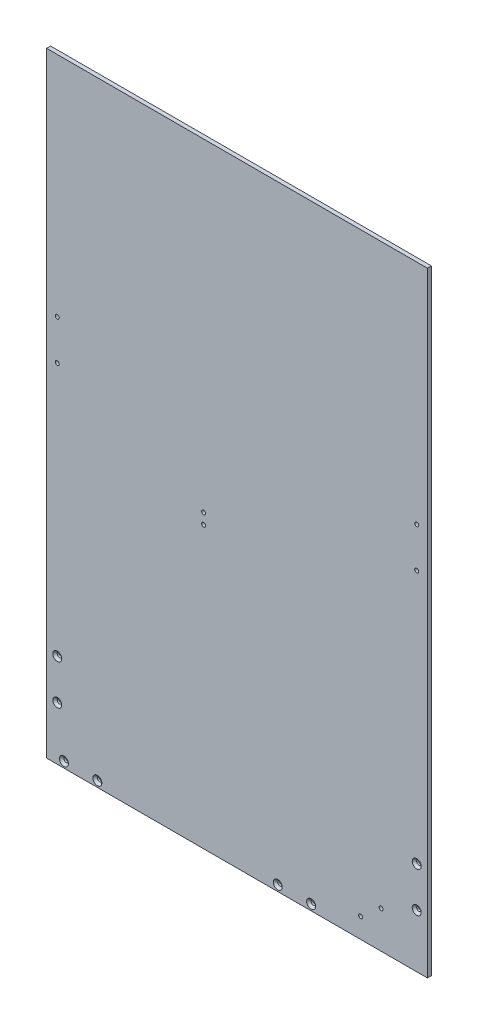
SolidWorks part; units mm, degrees
material "ABS PC"
ref_plane "前视基准面" through (0, 0, 0) normal (0, 0, 1) x (1, 0, 0)
ref_plane "上视基准面" through (0, 0, 0) normal (0, 1, 0) x (1, 0, 0)
ref_plane "右视基准面" through (0, 0, 0) normal (1, 0, 0) x (0, 0, -1)
sketch "草图1" plane through (0, 0, 0) normal (0, 0, 1) x (1, 0, 0)
  line L1 (-142.5, 230) -> (142.5, 230)
  line L2 (-142.5, 230) -> (-142.5, -230)
  line L3 (-142.5, -230) -> (142.5, -230)
  line L4 (142.5, 230) -> (142.5, -230)
  line L5 (-142.5, 230) -> (142.5, -230) construction
  line L6 (-142.5, -230) -> (142.5, 230) construction
  point P0 (0, 0)
  dimension "D1" = 460
  dimension "D2" = 285
extrude "凸台-拉伸1" add sketch "草图1" along normal blind 3
sketch "草图2" plane through (0, 0, 3) normal (0, 0, 1) x (1, 0, 0)
  line L0 (0, 230) -> (0, -230) construction
  line L1 (142.5, 230) -> (-142.5, 230) construction
  line L2 (-142.5, -230) -> (142.5, -230) construction
  line L3 (-134.5, 230) -> (-134.5, -230) construction
  line L4 (134.5, 230) -> (134.5, -230) construction
  line L5 (-142.5, 230) -> (-142.5, -230) construction
  circle A0 centre (-134.5, -190) radius 1.5
  circle A1 centre (134.5, -190) radius 1.5
  circle A2 centre (-134.5, -160) radius 1.5
  circle A3 centre (134.5, -160) radius 1.5
  circle A4 centre (-134.5, 30) radius 1.5
  circle A5 centre (134.5, 30) radius 1.5
  circle A6 centre (-134.5, 60) radius 1.5
  circle A7 centre (134.5, 60) radius 1.5
  dimension "D2" = 30
  dimension "D6" = 3
  dimension "D1" = 8
  dimension "D3" = 30
  dimension "D4" = 40
  dimension "D5" = 190
extrude "切除-拉伸1" cut sketch "草图2" against normal through all
sketch "草图4" plane through (0, 0, 3) normal (0, 0, 1) x (1, 0, 0)
  line L0 (-142.5, -230) -> (142.5, -230) construction
  line L1 (142.5, -230) -> (142.5, 230) construction
  line L2 (-129.5, -225.5) -> (-104.5, -225.5) construction
  line L3 (-142.5, -230) -> (142.5, -230) construction
  line L5 (55.5, -225.5) -> (30.5, -225.5) construction
  circle A0 centre (-129.5, -225.5) radius 1.5
  circle A2 centre (-104.5, -225.5) radius 1.5
  circle A3 centre (30.5, -225.5) radius 1.5
  circle A5 centre (55.5, -225.5) radius 1.5
  dimension "D2" = 25
  dimension "D6" = 160
  dimension "D4" = 3
  dimension "D3" = 25
  dimension "D5" = 4.5
  dimension "D7" = 87
  dimension "D11" = 4.5
extrude "切除-拉伸2" cut sketch "草图4" against normal through all
sketch "草图6" plane through (0, 0, 0) normal (0, 0, -1) x (-1, 0, 0)
  line L0 (25, 190) -> (25, -190) construction
  line L1 (142.5, 230) -> (142.5, -230) construction
  line L2 (142.5, -230) -> (-142.5, -230) construction
  circle A0 centre (25, -20) radius 1.5
  circle A1 centre (25, -12) radius 1.5
  dimension "D1" = 3
  dimension "D2" = 8
  dimension "D3" = 210
  dimension "D4" = 117.5
extrude "切除-拉伸3" cut sketch "草图6" against normal through all
sketch "草图7" plane through (0, 0, 0) normal (0, 0, -1) x (-1, 0, 0)
  line L0 (67.5, 230) -> (67.5, -230) construction
  line L1 (-142.5, 230) -> (142.5, 230) construction
  line L2 (142.5, -230) -> (-142.5, -230) construction
  line L3 (142.5, 230) -> (142.5, -230) construction
  circle A0 centre (67.5, -157) radius 9.5 construction
  circle A1 centre (67.5, -166.5) radius 1.5
  circle A2 centre (59.2728, -152.25) radius 1.5
  circle A3 centre (75.7272, -152.25) radius 1.5
  circle A4 centre (67.5, -157) radius 6.75
  point P18 (67.5, -157)
  dimension "D1" = 19
  dimension "D4" = 3
  dimension "D6" = 13.5
  dimension "D2" = 75
  dimension "D3" = 73
  dimension "D5" = 3
extrude "切除-拉伸4" [suppressed] cut sketch "草图7" against normal through all
sketch "草图8" plane through (0, 0, 0) normal (0, 0, -1) x (-1, 0, 0)
  line L0 (142.5, -230) -> (-142.5, -230) construction
  line L3 (-142.5, -230) -> (-142.5, 230) construction
  line L5 (-92.5, -215) -> (-107.8209, -202.1442) construction
  line L6 (-142.5, -230) -> (-142.5, 230) construction
  circle A2 centre (-107.8209, -202.1442) radius 1.5
  circle A3 centre (-92.5, -215) radius 1.5
  dimension "D9" = 3
  dimension "D7" = 50
  dimension "D8" = 50
  dimension "D10" = 15
  dimension "D11" = 20
extrude "切除-拉伸5" cut sketch "草图8" against normal through all
hole_wizard "M3 六角凹锥坑螺钉的锥形沉头孔1" positions "3D草图1" profile "草图9" countersink size "M3" standard "ISO" end condition through all
sketch3d "3D草图1"
  line L0 (-134.5, -160, 0) -> (-134.5, -160, 3) construction
  line L1 (-134.5, -190, 0) -> (-134.5, -190, 3) construction
  line L2 (134.5, -160, 0) -> (134.5, -160, 3) construction
  line L3 (134.5, -190, 0) -> (134.5, -190, 3) construction
  line L4 (-129.5, -225.5, 0) -> (-129.5, -225.5, 3) construction
  line L5 (-104.5, -225.5, 0) -> (-104.5, -225.5, 3) construction
  line L6 (30.5, -225.5, 0) -> (30.5, -225.5, 3) construction
  line L7 (55.5, -225.5, 0) -> (55.5, -225.5, 3) construction
  point P0 (-134.5, -160, 3)
  point P4 (-134.5, -190, 3)
  point P8 (134.5, -160, 3)
  point P12 (134.5, -190, 3)
  point P16 (-129.5, -225.5, 3)
  point P20 (-104.5, -225.5, 3)
  point P24 (30.5, -225.5, 3)
  point P28 (55.5, -225.5, 3)
sketch "草图9" plane through (-134.5, -160, 3) normal (1, 0, 0) x (0, -1, 0)
  line L0 (0, 0) -> (0, 3)
  line L1 (0, 3) -> (1.7, 3)
  line L2 (1.7, 3) -> (1.7, 1.66)
  line L3 (1.7, 1.66) -> (3.36, 0)
  line L5 (3.36, 0) -> (0, 0)
  line L6 (-1.7, 1.66) -> (-3.36, 0) construction
  line L11 (0, -6.35) -> (0, 107.95) construction
  dimension "通孔孔直径" = 3.4
  dimension "通孔孔深度" = 3
  dimension "近端锥形沉头孔直径" = 6.72
  dimension "近端锥形沉头孔角度" = 90
